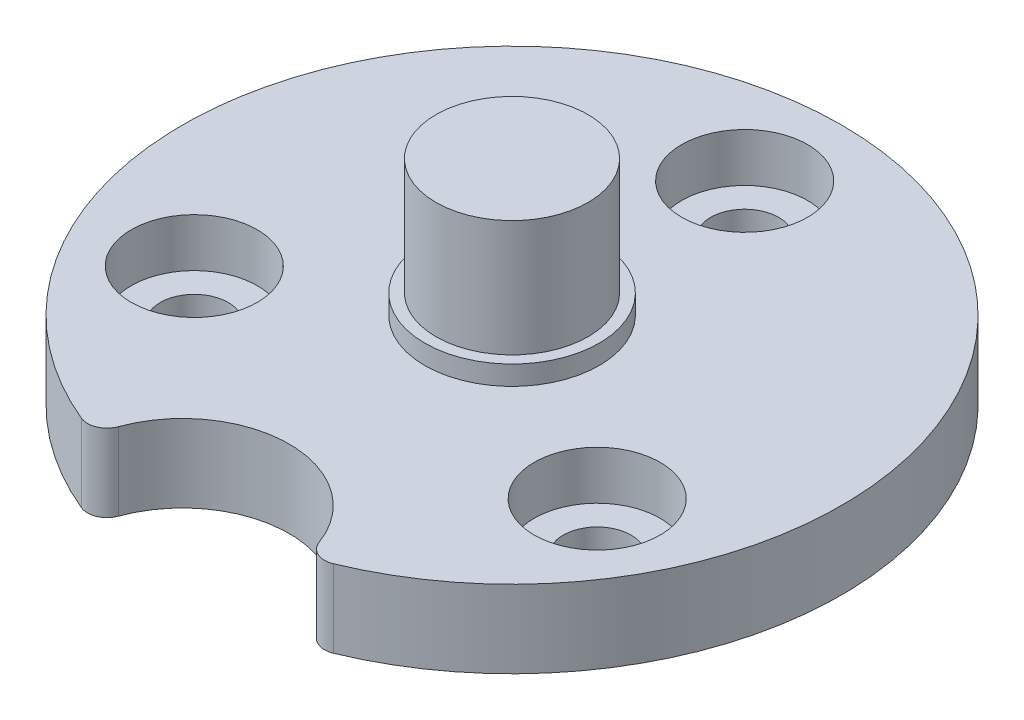
SolidWorks part; units mm, degrees
ref_plane "Front Plane" through (0, 0, 0) normal (0, 0, 1) x (1, 0, 0)
ref_plane "Top Plane" through (0, 0, 0) normal (0, 1, 0) x (1, 0, 0)
ref_plane "Right Plane" through (0, 0, 0) normal (1, 0, 0) x (0, 0, -1)
sketch "Sketch1" plane through (0, 0, 0) normal (0, 1, 0) x (1, 0, 0)
  line L0 (0, 0) -> (0, 15.6071) construction
  circle A0 centre (0, 0) radius 17
  circle A1 centre (0, 12) radius 1.75
  circle A2 centre (10.3923, -6) radius 1.75
  circle A3 centre (-10.3923, -6) radius 1.75
  point P12 (0, 0)
  dimension "D1" = 34
  dimension "D3" = 3.5
  dimension "D2" = 12
  dimension "D4" = 3
extrude "Boss-Extrude1" add sketch "Sketch1" along normal blind 4
sketch "Sketch2" plane through (0, 4, 0) normal (0, 1, 0) x (1, 0, 0)
  circle A0 centre (0, 12) radius 3.25
  circle A1 centre (10.3923, -6) radius 3.25
  circle A2 centre (-10.3923, -6) radius 3.25
  point P9 (0, 0)
  dimension "D1" = 6.5
  dimension "D2" = 3
extrude "Cut-Extrude1" cut sketch "Sketch2" against normal blind 2.5
sketch "Sketch3" plane through (0, 4, 0) normal (0, 1, 0) x (1, 0, 0)
  circle A0 centre (0, 0) radius 4.5
  dimension "D1" = 9
extrude "Boss-Extrude2" add sketch "Sketch3" along normal blind 1
sketch "Sketch4" plane through (0, 5, 0) normal (0, 1, 0) x (1, 0, 0)
  circle A0 centre (0, 0) radius 3.925
  dimension "D1" = 7.85
extrude "Boss-Extrude3" add sketch "Sketch4" along normal blind 6
sketch "Sketch5" plane through (0, 4, 0) normal (0, 1, 0) x (1, 0, 0)
  circle A0 centre (0, -17) radius 5.5
  dimension "D1" = 11
  dimension "D2" = 17
extrude "Cut-Extrude2" cut sketch "Sketch5" against normal up to next
fillet "Fillet1" radius 1 2 edges at (-5.4276, 2, 16.1103) (5.4276, 2, 16.1103)
